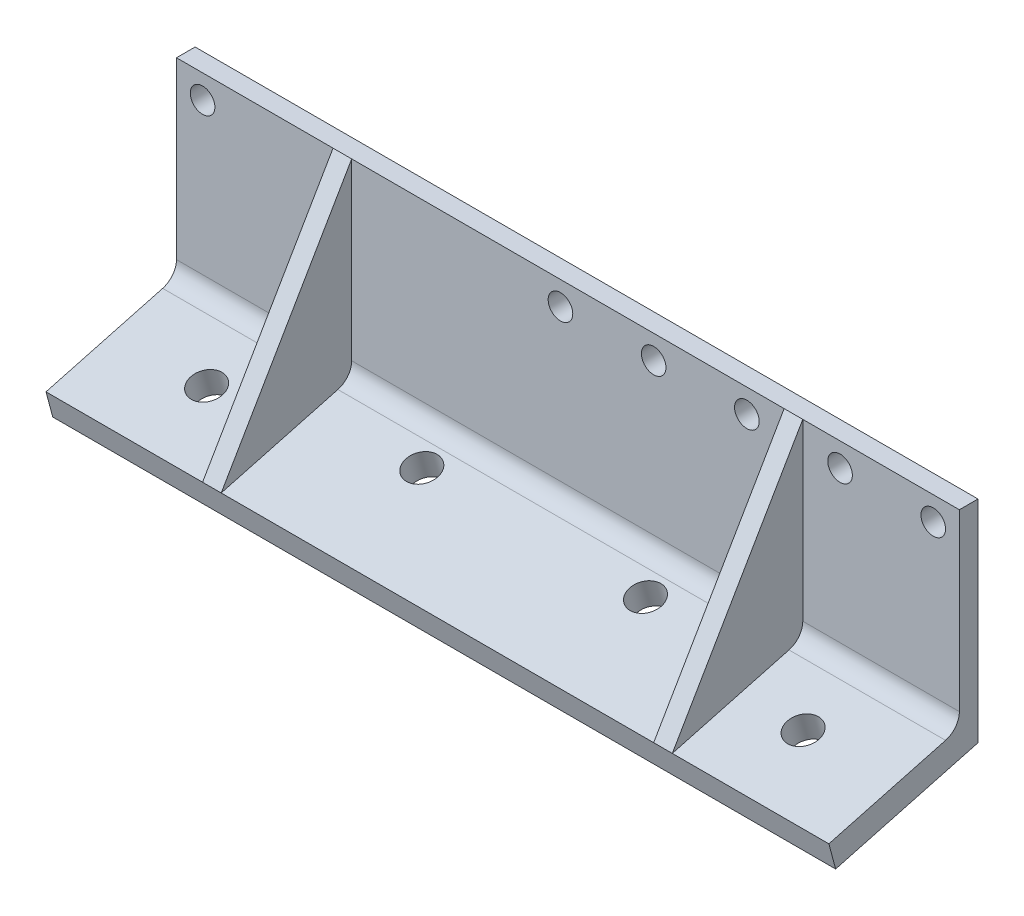
SolidWorks part; units mm, degrees
material "1060 合金"
ref_plane "前视基准面" through (0, 0, 0) normal (0, 0, 1) x (1, 0, 0)
ref_plane "上视基准面" through (0, 0, 0) normal (0, 1, 0) x (1, 0, 0)
ref_plane "右视基准面" through (0, 0, 0) normal (1, 0, 0) x (0, 0, -1)
sketch "草图1" plane through (0, 0, 0) normal (0, 1, 0) x (1, 0, 0)
  line L0 (0, 0) -> (170, 0) construction
  line L1 (170, 31.93) -> (170, -31.93)
  line L2 (15.8391, 73.3084) -> (162.1119, 41.7045)
  line L3 (15.8391, -73.3084) -> (162.1119, -41.7045)
  arc A0 (15.8391, 73.3084) -> (15.8391, -73.3084) centre (0, 0) ccw
  arc A1 (162.1119, -41.7045) -> (170, -31.93) centre (160, -31.93) ccw
  arc A2 (170, 31.93) -> (162.1119, 41.7045) centre (160, 31.93) ccw
  point P6 (170, 0)
  dimension "D1" = 150
  dimension "D4" = 20
  dimension "D5" = 20
  dimension "D2" = 170
  dimension "D3" = 63.86
extrude "凸台-拉伸1" add sketch "草图1" along normal blind 30
sketch "草图2" plane through (0, 30, 0) normal (0, 1, 0) x (1, 0, 0)
  circle A0 centre (0, 0) radius 44.45
  dimension "D1" = 88.9
extrude "切除-拉伸1" cut sketch "草图2" against normal blind 4
sketch "草图3" plane through (0, 26, 0) normal (0, 1, 0) x (1, 0, 0)
  line L0 (0, 0) -> (0, 90.3276) construction
  circle A0 centre (0, 0) radius 25.5
  circle A1 centre (0, 41) radius 2.25
  circle A2 centre (28.9914, 28.9914) radius 2.25
  circle A3 centre (41, 0) radius 2.25
  circle A4 centre (28.9914, -28.9914) radius 2.25
  circle A5 centre (0, -41) radius 2.25
  circle A6 centre (-28.9914, -28.9914) radius 2.25
  circle A7 centre (-41, 0) radius 2.25
  circle A8 centre (-28.9914, 28.9914) radius 2.25
  dimension "D1" = 51
  dimension "D3" = 4.5
  dimension "D2" = 41
  dimension "D4" = 8
extrude "切除-拉伸2" cut sketch "草图3" against normal through all contours A2 | A3 | A4 | A5 | A6 | A7 | A8 | A1 | A0
sketch "草图4" plane through (0, 30, 0) normal (0, 1, 0) x (1, 0, 0)
  line L0 (0, 0) -> (134, 0) construction
  line L1 (124, 18.5) -> (134, 18.5)
  line L2 (124, -18.5) -> (134, -18.5)
  arc A0 (134, -18.5) -> (134, 18.5) centre (134, 0) ccw
  arc A1 (124, 18.5) -> (124, -18.5) centre (124, 0) ccw
  dimension "D2" = 37
  dimension "D3" = 37
  dimension "D1" = 134
  dimension "D4" = 10
extrude "切除-拉伸3" cut sketch "草图4" against normal through all
sketch "草图5" plane through (0, 30, 0) normal (0, 1, 0) x (1, 0, 0)
  arc A0 (134, -18.5) -> (134, 18.5) centre (134, 0) ccw construction
  arc A1 (124, 18.5) -> (124, -18.5) centre (124, 0) ccw construction
  arc A2 (134, -18.5) -> (134, 18.5) centre (134, 0) ccw construction
  arc A3 (124, 18.5) -> (124, -18.5) centre (124, 0) ccw construction
  circle A4 centre (116.75, 25.5) radius 1.65
  circle A5 centre (141.25, 25.5) radius 1.65
  circle A6 centre (141.25, -25.5) radius 1.65
  circle A7 centre (116.75, -25.5) radius 1.65
  dimension "D1" = 3.3
  dimension "D2" = 3.3
  dimension "D3" = 3.3
  dimension "D4" = 3.3
  dimension "D7" = 25.5
  dimension "D5" = 7.25
  dimension "D6" = 25.5
  dimension "D8" = 7.25
  dimension "D9" = 7.25
extrude "切除-拉伸4" cut sketch "草图5" against normal through all
sketch "草图6" plane through (0, 30, 0) normal (0, 1, 0) x (1, 0, 0)
  line L0 (158, 42.5929) -> (158, -42.5929) construction
  line L2 (-52, 54.0463) -> (-52, -54.0463) construction
  line L6 (162.1119, 41.7045) -> (15.8391, 73.3084) construction
  line L7 (15.8391, -73.3084) -> (162.1119, -41.7045) construction
  line L8 (-52, 95) -> (-52, -95)
  line L9 (158, 95) -> (158, -95)
  line L10 (-52, 95) -> (158, 95)
  line L11 (-52, -95) -> (158, -95)
  line L15 (162.1119, 41.7045) -> (15.8391, 73.3084)
  line L16 (15.8391, -73.3084) -> (162.1119, -41.7045)
  line L17 (170, -31.93) -> (170, 31.93)
  line L18 (162.1119, 41.7045) -> (15.8391, 73.3084)
  line L19 (15.8391, -73.3084) -> (162.1119, -41.7045)
  line L20 (170, -31.93) -> (170, 31.93)
  arc A0 (15.8391, 73.3084) -> (15.8391, -73.3084) centre (0, 0) ccw construction
  arc A6 (170, 31.93) -> (162.1119, 41.7045) centre (160, 31.93) ccw
  arc A7 (15.8391, 73.3084) -> (15.8391, -73.3084) centre (0, 0) ccw
  arc A8 (162.1119, -41.7045) -> (170, -31.93) centre (160, -31.93) ccw
  arc A9 (170, 31.93) -> (162.1119, 41.7045) centre (160, 31.93) ccw
  arc A10 (15.8391, 73.3084) -> (15.8391, -73.3084) centre (0, 0) ccw
  arc A11 (162.1119, -41.7045) -> (170, -31.93) centre (160, -31.93) ccw
  point P8 (-52, 0)
  point P13 (158, 0)
  line M26 (162.1119, 41.7045) -> (15.8391, 73.3084)
  arc M27 (15.8391, 73.3084) -> (15.8391, -73.3084) centre (0, 0) ccw
  line M28 (15.8391, -73.3084) -> (162.1119, -41.7045)
  dimension "D3" = 190
  dimension "D1" = 210
  dimension "D2" = 52
  dimension "D4" = 190
  dimension "D5" = 0
extrude "凸台-拉伸2" add sketch "草图6" against normal blind 30 contours L10 L8 L9 M27 M26 | L8 L11 L9 M28 M27
sketch "草图7" plane through (0, 30, 0) normal (0, 1, 0) x (1, 0, 0)
  line L0 (-52, 54.0463) -> (-52, -54.0463)
  line L1 (158, 42.5929) -> (158, -42.5929)
  line L9 (162.1119, 41.7045) -> (158, 42.5929)
  line L10 (158, 42.5929) -> (158, 95)
  line L11 (158, 95) -> (-52, 95)
  line L12 (-52, 95) -> (-52, 54.0463)
  line L13 (-52, -54.0463) -> (-52, -95)
  line L14 (-52, -95) -> (158, -95)
  line L15 (158, -95) -> (158, -42.5929)
  line L16 (158, -42.5929) -> (162.1119, -41.7045)
  line L17 (170, -31.93) -> (170, 31.93)
  line L18 (162.1119, 41.7045) -> (158, 42.5929)
  line L21 (-52, 95) -> (-52, 54.0463)
  line L25 (158, -42.5929) -> (162.1119, -41.7045)
  line L26 (170, -31.93) -> (170, 31.93)
  arc A3 (170, 31.93) -> (162.1119, 41.7045) centre (160, 31.93) ccw
  arc A4 (-52, 54.0463) -> (-52, -54.0463) centre (0, 0) ccw
  arc A5 (162.1119, -41.7045) -> (170, -31.93) centre (160, -31.93) ccw
  arc A6 (170, 31.93) -> (162.1119, 41.7045) centre (160, 31.93) ccw
  arc A7 (-52, 54.0463) -> (-52, -54.0463) centre (0, 0) ccw
  arc A8 (162.1119, -41.7045) -> (170, -31.93) centre (160, -31.93) ccw
  arc M22 (170, 31.93) -> (162.1119, 41.7045) centre (160, 31.93) ccw
  line M23 (162.1119, 41.7045) -> (158, 42.5929)
  arc M27 (-52, 54.0463) -> (-52, -54.0463) centre (0, 0) ccw
  line M31 (158, -42.5929) -> (162.1119, -41.7045)
  arc M32 (162.1119, -41.7045) -> (170, -31.93) centre (160, -31.93) ccw
  line M33 (170, -31.93) -> (170, 31.93)
  dimension "D1" = 0
extrude "切除-拉伸5" cut sketch "草图7" against normal through all contours L0 M27 | L1 M23 M31 M32 M33 M22
sketch "草图9" plane through (-52, 0, 0) normal (-1, 0, 0) x (0, 0, 1)
  line L0 (-95, 20) -> (-60, 10.6218)
  line L1 (-95, 30) -> (95, 30) construction
  line L3 (-60, 10.6218) -> (-60, 30)
  line L5 (-95, 0) -> (-95, 30) construction
  line L7 (-95, 20) -> (-95, 30)
  line L8 (-95, 30) -> (-60, 30)
  dimension "D1" = 15
  dimension "D3" = 19.3782
  dimension "D4" = 35
  dimension "D5" = 10
extrude "切除-拉伸7" cut sketch "草图9" against normal through all contours L8 L3 L0 L7
sketch "草图8" plane through (-52, 0, 0) normal (-1, 0, 0) x (0, 0, 1)
  line L0 (0, 0) -> (52, 0)
  line L1 (-95, 0) -> (95, 0) construction
  line L2 (52, 0) -> (52, 17.3)
  line L3 (52, 17.3) -> (-52, 17.3)
  line L4 (-52, 17.3) -> (-52, 0)
  line L5 (-52, 0) -> (0, 0)
  line L6 (-60, 30) -> (95, 30) construction
  dimension "D1" = 52
  dimension "D2" = 52
  dimension "D3" = 12.7
sketch "草图10" plane through (-52, 0, 0) normal (-1, 0, 0) x (0, 0, 1)
  line L0 (-95, 12.7531) -> (-47.4049, 0) construction
  line L1 (-95, 0) -> (-95, 20) construction
  line L2 (-95, 0) -> (95, 0) construction
  line L3 (-95, 20) -> (-60, 10.6218) construction
  line L6 (-95, 12.7531) -> (-52, 1.2313)
  line L7 (-52, 1.2313) -> (-52, 0)
  line L8 (-95, 12.7531) -> (-95, 0)
  line L9 (-95, 0) -> (-52, 0)
  line L10 (-52, 17.3) -> (-52, 0) construction
  dimension "D1" = 7
extrude "切除-拉伸8" cut sketch "草图10" against normal through all
extrude "切除-拉伸9" cut sketch "草图8" against normal through all
fillet "圆角1" radius 5 1 edges at (53, 10.6218, -60)
sketch "草图11" plane through (-52, 0, 0) normal (-1, 0, 0) x (0, 0, 1)
  line L0 (-95, 12.7531) -> (-93.1883, 19.5145)
  line L1 (-95, 20) -> (-66.2941, 12.3083) construction
  line L2 (-93.1883, 19.5145) -> (-95, 20)
  line L3 (-95, 20) -> (-95, 12.7531)
extrude "切除-拉伸10" cut sketch "草图11" against normal through all
sketch "草图12" plane through (-52, 0, 0) normal (-1, 0, 0) x (0, 0, 1)
  line L0 (-93.1883, 19.5145) -> (-60, 30)
  line L10 (-93.1883, 19.5145) -> (-95, 12.7531)
  line L11 (-95, 12.7531) -> (-52, 1.2313)
  line L12 (-52, 1.2313) -> (-52, 17.3)
  line L13 (-52, 17.3) -> (52, 17.3)
  line L14 (52, 17.3) -> (52, 0)
  line L15 (52, 0) -> (95, 0)
  line L16 (95, 0) -> (95, 30)
  line L17 (95, 30) -> (-60, 30)
  line L18 (-60, 30) -> (-60, 17.1379)
  line L19 (-66.2941, 12.3083) -> (-93.1883, 19.5145)
  line L28 (-60, 30) -> (-60, 17.1379)
  line L29 (-66.2941, 12.3083) -> (-93.1883, 19.5145)
  arc A1 (-66.2941, 12.3083) -> (-60, 17.1379) centre (-65, 17.1379) ccw
  arc A2 (-66.2941, 12.3083) -> (-60, 17.1379) centre (-65, 17.1379) ccw
  dimension "D1" = 0
extrude "凸台-拉伸3" add sketch "草图12" against normal blind 5
sketch "草图13" plane through (158, 0, 0) normal (1, 0, 0) x (0, 0, -1)
  line L3 (66.2941, 12.3083) -> (93.1883, 19.5145)
  line L4 (93.1883, 19.5145) -> (60, 30)
  line L5 (60, 30) -> (60, 17.1379)
  line L6 (66.2941, 12.3083) -> (93.1883, 19.5145)
  line L7 (93.1883, 19.5145) -> (60, 30)
  line L8 (60, 30) -> (60, 17.1379)
  arc A1 (60, 17.1379) -> (66.2941, 12.3083) centre (65, 17.1379) ccw
  arc A2 (60, 17.1379) -> (66.2941, 12.3083) centre (65, 17.1379) ccw
  dimension "D1" = 0
extrude "凸台-拉伸4" add sketch "草图13" against normal blind 5
sketch "草图14" plane through (0, -5.0897, -1.3638) normal (0, 0.9659, 0.2588) x (1, 0, 0)
  line L0 (153, 67.2208) -> (153, 95.0637) construction
  line L3 (153, 95.0637) -> (-47, 95.0637) construction
  circle A0 centre (-27, 82.0637) radius 4.25
  circle A1 centre (23, 82.0637) radius 4.25
  circle A2 centre (83, 82.0637) radius 4.25
  circle A3 centre (133, 82.0637) radius 4.25
  dimension "D1" = 8.5
  dimension "D2" = 160
  dimension "D3" = 20
  dimension "D4" = 50
  dimension "D5" = 50
  dimension "D6" = 13
extrude "切除-拉伸11" cut sketch "草图14" against normal through all
sketch "草图16" plane through (-52, 0, 0) normal (-1, 0, 0) x (0, 0, 1)
  line L0 (-60, 30) -> (95, 30) construction
  line L1 (95, 0) -> (52, 0)
  line L2 (95, 0) -> (95, 30)
  line L3 (95, 30) -> (52, 30)
  line L4 (52, 0) -> (52, 30)
extrude "切除-拉伸12" cut sketch "草图16" against normal through all
ref_plane "基准面1" through (0, -11.8512, -3.1755) normal (0, -0.9659, -0.2588) x (-1, 0, 0)
sketch "草图18" plane through (0, 30, 0) normal (0, 1, 0) x (1, 0, 0)
  line L1 (-52, -52) -> (158, -52)
  line L2 (-52, -52) -> (-52, -57)
  line L3 (-52, -57) -> (158, -57)
  line L4 (158, -52) -> (158, -57)
  dimension "D1" = 5
extrude "凸台-拉伸7" add sketch "草图18" against normal up to surface (56.6355 mm away) up to plane "基准面1"
sketch "草图19" plane through (-52, 0, 0) normal (-1, 0, 0) x (0, 0, 1)
  line L0 (57, -27.9752) -> (90.1883, -36.868)
  line L1 (90.1883, -36.868) -> (92, -30.1065)
  line L2 (92, -30.1065) -> (57, -20.7283)
  line L3 (57, -27.9752) -> (57, 30) construction
  line L4 (57, -20.7283) -> (57, -27.9752)
  line L5 (52, -26.6355) -> (57, -27.9752) construction
  dimension "D1" = 7
  dimension "D2" = 40
extrude "凸台-拉伸8" add sketch "草图19" against normal up to surface (210 mm away) up to face at (158, 8.1654, -14.9098)
sketch "草图20" plane through (-52, 0, 0) normal (-1, 0, 0) x (0, 0, 1)
  line L0 (92, -30.1065) -> (57, -20.7283) construction
  line L1 (57, -20.7283) -> (57, 30) construction
  line L2 (92, -30.1065) -> (57, -20.7283)
  line L3 (57, -20.7283) -> (57, 30)
  line L4 (57, 30) -> (92, -30.1065)
extrude "凸台-拉伸9" add sketch "草图20" against normal blind 5
sketch "草图21" plane through (158, 0, 0) normal (1, 0, 0) x (0, 0, -1)
  line L3 (-57, 30) -> (-92, -30.1065)
  line L4 (-92, -30.1065) -> (-57, -20.7283)
  line L5 (-57, -20.7283) -> (-57, 30)
  line L6 (-57, 30) -> (-92, -30.1065)
  line L7 (-92, -30.1065) -> (-57, -20.7283)
  line L8 (-57, -20.7283) -> (-57, 30)
  dimension "D1" = 0
extrude "凸台-拉伸10" add sketch "草图21" against normal blind 5
sketch "草图22" plane through (0, -5.0897, -1.3638) normal (0, 0.9659, 0.2588) x (1, 0, 0)
  line L0 (-47, -96.6573) -> (-47, -47.2932) construction
  line L2 (153, -96.6573) -> (153, -60.4226) construction
  circle A0 centre (-27, -77.9363) radius 4.25
  circle A1 centre (23, -69.9363) radius 4.25
  circle A2 centre (83, -69.9363) radius 4.25
  circle A3 centre (133, -77.9363) radius 4.25
  circle A4 centre (133, 82.0637) radius 4.25 construction
  circle A5 centre (-27, 82.0637) radius 4.25 construction
  circle A6 centre (23, 82.0637) radius 4.25 construction
  circle A7 centre (83, 82.0637) radius 4.25 construction
  dimension "D1" = 8.5
  dimension "D7" = 152
  dimension "D6" = 152
  dimension "D8" = 50
  dimension "D4" = 160
  dimension "D5" = 160
  dimension "D2" = 20
  dimension "D3" = 20
  dimension "D9" = 50
extrude "切除-拉伸13" cut sketch "草图22" against normal through all
fillet "圆角2" radius 5 1 edges at (53, -20.7283, 57)
sketch "草图23" plane through (-52, 0, 0) normal (-1, 0, 0) x (0, 0, 1)
  line L0 (52, -26.6355) -> (52, 17.3) construction
  line L1 (52, 56.9656) -> (-106.5122, 56.9656)
  line L2 (52, 56.9656) -> (52, -46.3521)
  line L3 (52, -46.3521) -> (-106.5122, -46.3521)
  line L4 (-106.5122, 56.9656) -> (-106.5122, -46.3521)
extrude "切除-拉伸14" cut sketch "草图23" against normal through all
sketch "草图24" plane through (0, 0, 57) normal (0, 0, 1) x (1, 0, 0)
  line L1 (-47, 30) -> (153, 30) construction
  circle A0 centre (-45, 23.65) radius 3.3
  circle A1 centre (151, 23.65) radius 3.3
  circle A2 centre (126, 23.65) radius 3.3
  circle A3 centre (101, 23.65) radius 3.3
  circle A4 centre (76, 23.65) radius 3.3
  circle A5 centre (51, 23.65) radius 3.3
  dimension "D1" = 6.6
  dimension "D2" = 7
  dimension "D3" = 7
  dimension "D4" = 25
  dimension "D5" = 25
  dimension "D6" = 25
  dimension "D7" = 25
  dimension "D8" = 6.35
ref_plane "基准面2" through (113.5, 0, 0) normal (1, 0, 0) x (0, 0, -1)
sketch "草图25" plane through (113.5, 0, 0) normal (1, 0, 0) x (0, 0, -1)
  line L3 (-57, -16.8916) -> (-57, 30)
  line L4 (-92, -30.1065) -> (-60.7059, -21.7213)
  line L5 (-57, 30) -> (-92, -30.1065)
  line L6 (-57, -16.8916) -> (-57, 30)
  line L7 (-92, -30.1065) -> (-60.7059, -21.7213)
  line L8 (-57, 30) -> (-92, -30.1065)
  arc A1 (-60.7059, -21.7213) -> (-57, -16.8916) centre (-62, -16.8916) ccw
  arc A2 (-60.7059, -21.7213) -> (-57, -16.8916) centre (-62, -16.8916) ccw
  dimension "D1" = 0
extrude "凸台-拉伸11" add sketch "草图25" along normal mid plane 5
ref_plane "基准面3" through (-7.5, 0, 0) normal (-1, 0, 0) x (0, 0, 1)
sketch "草图26" plane through (-7.5, 0, 0) normal (-1, 0, 0) x (0, 0, 1)
  line L3 (60.7059, -21.7213) -> (92, -30.1065)
  line L4 (57, 30) -> (57, -16.8916)
  line L5 (92, -30.1065) -> (57, 30)
  line L6 (60.7059, -21.7213) -> (92, -30.1065)
  line L7 (57, 30) -> (57, -16.8916)
  line L8 (92, -30.1065) -> (57, 30)
  arc A1 (57, -16.8916) -> (60.7059, -21.7213) centre (62, -16.8916) ccw
  arc A2 (57, -16.8916) -> (60.7059, -21.7213) centre (62, -16.8916) ccw
  dimension "D1" = 0
extrude "凸台-拉伸12" add sketch "草图26" along normal mid plane 5
sketch "草图27" plane through (-47, 0, 0) normal (1, 0, 0) x (0, 0, -1)
  line L3 (-92, -30.1065) -> (-60.7059, -21.7213)
  line L4 (-57, -16.8916) -> (-57, 30)
  line L5 (-57, 30) -> (-92, -30.1065)
  line L6 (-92, -30.1065) -> (-60.7059, -21.7213)
  line L7 (-57, -16.8916) -> (-57, 30)
  line L8 (-57, 30) -> (-92, -30.1065)
  arc A1 (-60.7059, -21.7213) -> (-57, -16.8916) centre (-62, -16.8916) ccw
  arc A2 (-60.7059, -21.7213) -> (-57, -16.8916) centre (-62, -16.8916) ccw
  dimension "D1" = 0
extrude "切除-拉伸15" cut sketch "草图27" against normal blind 5
sketch "草图28" plane through (153, 0, 0) normal (-1, 0, 0) x (0, 0, 1)
  line L3 (57, 30) -> (57, -16.8916)
  line L4 (60.7059, -21.7213) -> (92, -30.1065)
  line L5 (92, -30.1065) -> (57, 30)
  line L6 (57, 30) -> (57, -16.8916)
  line L7 (60.7059, -21.7213) -> (92, -30.1065)
  line L8 (92, -30.1065) -> (57, 30)
  arc A1 (57, -16.8916) -> (60.7059, -21.7213) centre (62, -16.8916) ccw
  arc A2 (57, -16.8916) -> (60.7059, -21.7213) centre (62, -16.8916) ccw
  dimension "D1" = 0
extrude "切除-拉伸16" cut sketch "草图28" against normal blind 5
extrude "切除-拉伸17" cut sketch "草图24" against normal through all
